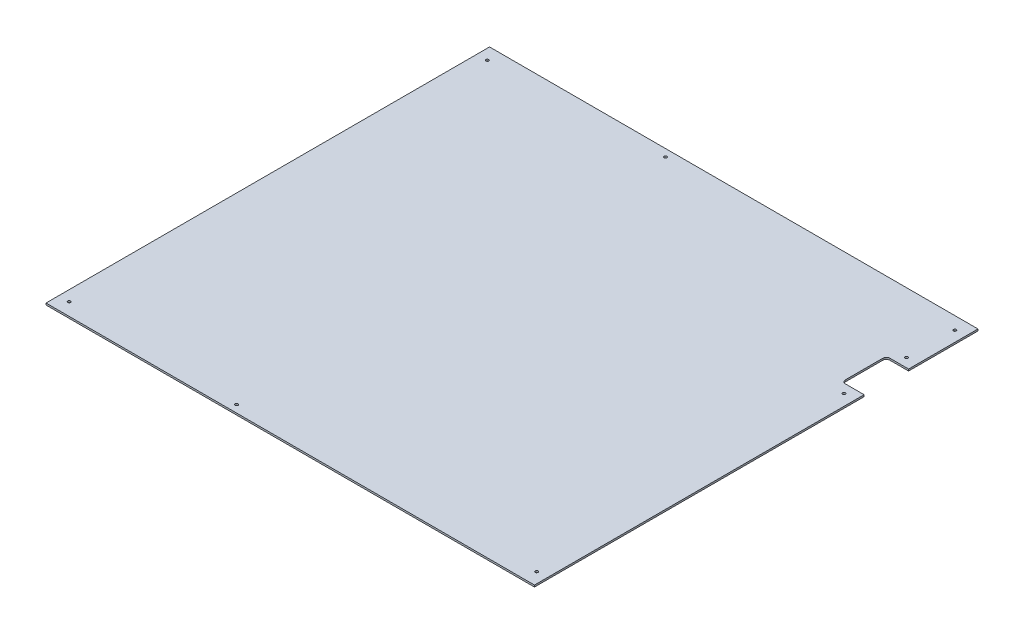
SolidWorks part; units mm, degrees
ref_plane "Alzado" through (0, 0, 0) normal (0, 0, 1) x (1, 0, 0)
ref_plane "Planta" through (0, 0, 0) normal (0, 1, 0) x (1, 0, 0)
ref_plane "Vista lateral" through (0, 0, 0) normal (1, 0, 0) x (0, 0, -1)
sketch "Croquis1" plane through (0, 0, 0) normal (0, 1, 0) x (1, 0, 0)
  line L1 (0, 0) -> (550.5, 0)
  line L2 (0, 0) -> (0, 500)
  line L3 (0, 500) -> (550.5, 500)
  line L4 (550.5, 0) -> (550.5, 500)
  dimension "D1" = 500
  dimension "D2" = 550.5
extrude "Saliente-Extruir1" add sketch "Croquis1" along normal blind 2
sketch "Croquis2" plane through (0, 2, 0) normal (0, 1, 0) x (1, 0, 0)
  line L0 (550.5, 500) -> (0, 500) construction
  line L1 (0, 500) -> (0, 0) construction
  line L2 (275.25, 500) -> (275.25, 0) construction
  line L3 (0, 0) -> (550.5, 0) construction
  line L4 (0, 250) -> (550.5, 250) construction
  line L5 (550.5, 0) -> (550.5, 500) construction
  circle A0 centre (12.5, 485) radius 1.55
  circle A1 centre (538, 485) radius 1.55
  circle A2 centre (538, 15) radius 1.55
  circle A3 centre (12.5, 15) radius 1.55
  dimension "D1" = 3.1
  dimension "D2" = 15
  dimension "D3" = 12.5
extrude "Cortar-Extruir1" cut sketch "Croquis2" against normal up to surface (2 mm away) up to face at (275.25, 0, -250)
sketch "Croquis3" plane through (0, 2, 0) normal (0, 1, 0) x (1, 0, 0)
  line L0 (549.75, 499.25) -> (0.75, 499.25)
  line L1 (0.75, 499.25) -> (0.75, 0.75)
  line L2 (0.75, 0.75) -> (549.75, 0.75)
  line L3 (549.75, 0.75) -> (549.75, 499.25)
  line L4 (0, 500) -> (0, 0)
  line L5 (0, 0) -> (550.5, 0)
  line L6 (550.5, 0) -> (550.5, 500)
  line L7 (550.5, 500) -> (0, 500)
  line L8 (0, 500) -> (0, 0)
  line L9 (0, 0) -> (550.5, 0)
  line L10 (550.5, 0) -> (550.5, 500)
  line L11 (550.5, 500) -> (0, 500)
  dimension "D1" = 0
  dimension "D2" = 0.75
extrude "Cortar-Extruir2" cut sketch "Croquis3" against normal up to surface (2 mm away) up to face at (12.5, 0, -16.55)
sketch "Croquis4" plane through (0, 2, 0) normal (0, 1, 0) x (1, 0, 0)
  line L0 (549.75, 0.75) -> (549.75, 499.25) construction
  line L1 (549.75, 421.25) -> (524.75, 421.25)
  line L2 (549.75, 421.25) -> (549.75, 371.25)
  line L3 (549.75, 371.25) -> (524.75, 371.25)
  line L4 (524.75, 421.25) -> (524.75, 371.25)
  line L5 (549.75, 499.25) -> (0.75, 499.25) construction
  dimension "D1" = 25
  dimension "D2" = 50
  dimension "D3" = 78
extrude "Cortar-Extruir3" cut sketch "Croquis4" against normal up to surface (2 mm away) up to face at (12.5, 0, -486.55)
fillet "Redondeo1" radius 4 2 edges at (524.75, 1, -371.25) (524.75, 1, -421.25)
sketch "Croquis5" plane through (0, 2, 0) normal (0, 1, 0) x (1, 0, 0)
  line L0 (549.75, 421.25) -> (528.75, 421.25) construction
  line L1 (549.75, 421.25) -> (549.75, 499.25) construction
  line L2 (528.75, 371.25) -> (549.75, 371.25) construction
  line L3 (549.75, 0.75) -> (549.75, 371.25) construction
  circle A0 centre (537.25, 431.25) radius 1.6
  circle A1 centre (537.25, 361.25) radius 1.6
  dimension "D1" = 3.2
  dimension "D2" = 10
  dimension "D3" = 12.5
  dimension "D4" = 10
  dimension "D5" = 12.5
extrude "Cortar-Extruir4" cut sketch "Croquis5" against normal up to surface (2 mm away) up to face at (430.5843, 0, -337.75)
sketch "Croquis6" plane through (0, 2, 0) normal (0, 1, 0) x (1, 0, 0)
  line L0 (549.75, 499.25) -> (0.75, 499.25) construction
  line L1 (0.75, 499.25) -> (0.75, 0.75) construction
  line L2 (0.75, 0.75) -> (549.75, 0.75) construction
  circle A0 centre (206.75, 491) radius 1.6
  circle A1 centre (206.75, 9) radius 1.6
  dimension "D1" = 3.2
  dimension "D4" = 3.2
  dimension "D2" = 8.25
  dimension "D3" = 206
  dimension "D5" = 8.25
  dimension "D6" = 206
extrude "Cortar-Extruir5" cut sketch "Croquis6" against normal up to surface (2 mm away) up to face at (537.25, 0, -432.85)
